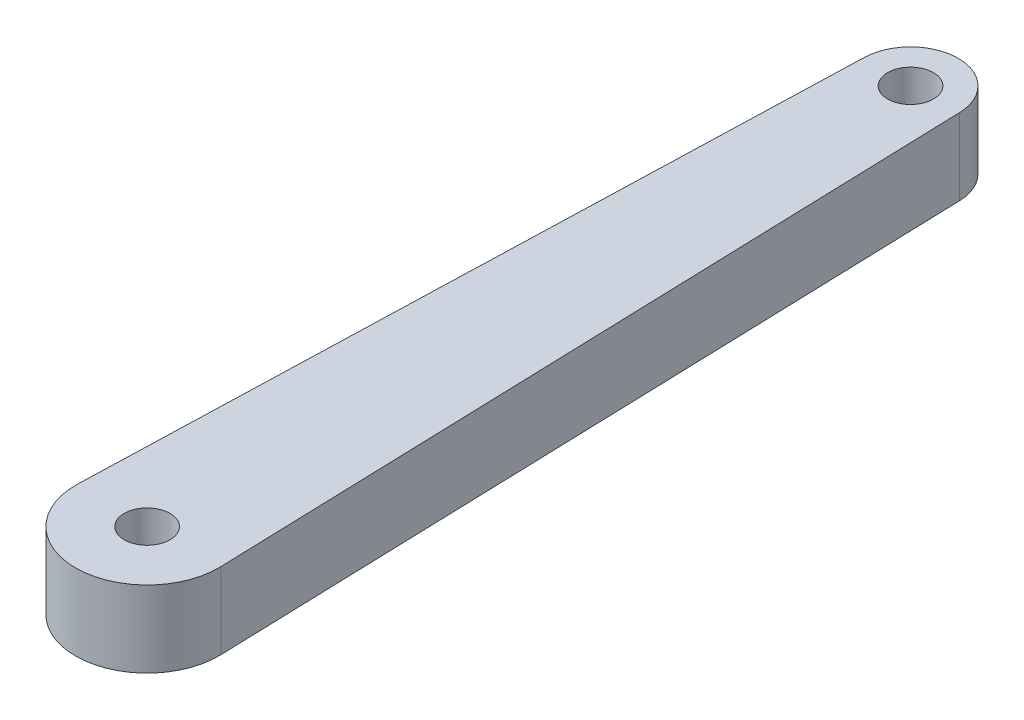
SolidWorks part; units mm, degrees
ref_plane "Front Plane" through (0, 0, 0) normal (0, 0, 1) x (1, 0, 0)
ref_plane "Top Plane" through (0, 0, 0) normal (0, 1, 0) x (1, 0, 0)
ref_plane "Right Plane" through (0, 0, 0) normal (1, 0, 0) x (0, 0, -1)
sketch "Sketch1" plane through (0, 0, 0) normal (0, 1, 0) x (1, 0, 0)
  line L0 (0, 0) -> (0, 40) construction
  line L1 (-3.7482, 0.1172) -> (-2.4988, 40.0781)
  line L2 (3.7482, 0.1172) -> (2.4988, 40.0781)
  circle A0 centre (0, 40) radius 2.5
  circle A1 centre (0, 0) radius 3.75
  circle A2 centre (0, 40) radius 1.2
  circle A3 centre (0, 0) radius 1.2
  dimension "D1" = 5
  dimension "D2" = 7.5
  dimension "D4" = 2.4
  dimension "D5" = 2.4
  dimension "D3" = 40
extrude "Boss-Extrude1" add sketch "Sketch1" along normal blind 4
